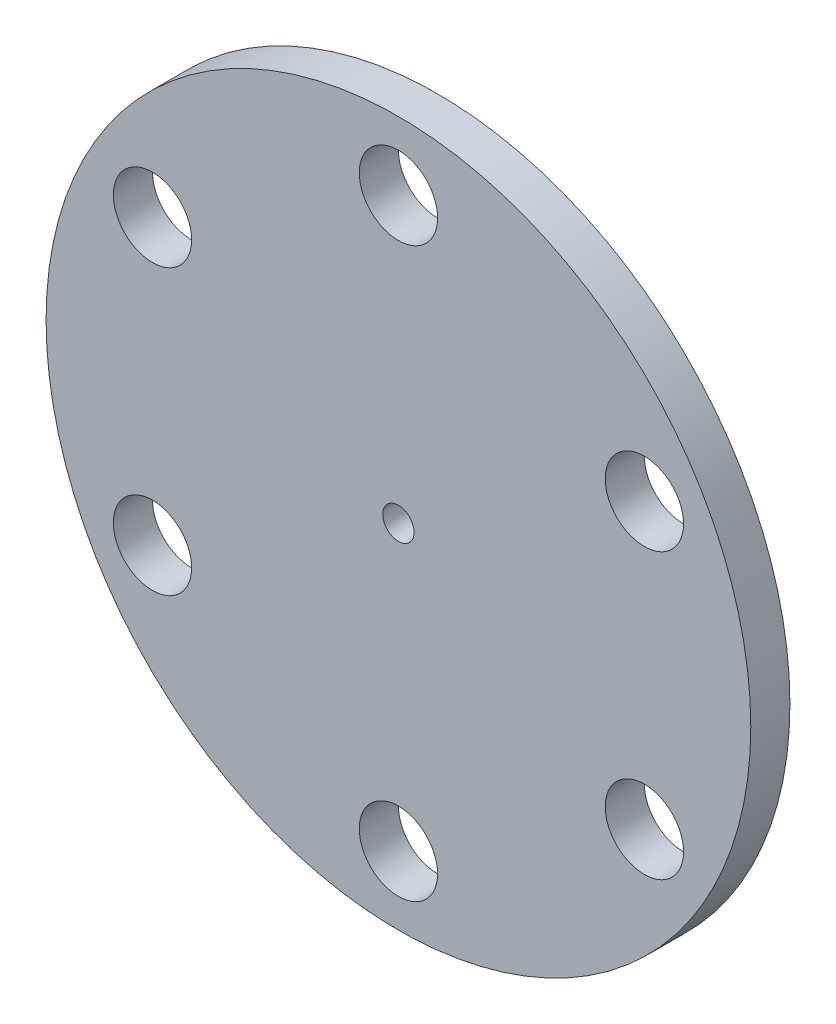
SolidWorks part; units mm, degrees
ref_plane "Front Plane" through (0, 0, 0) normal (0, 0, 1) x (1, 0, 0)
ref_plane "Top Plane" through (0, 0, 0) normal (0, 1, 0) x (1, 0, 0)
ref_plane "Right Plane" through (0, 0, 0) normal (1, 0, 0) x (0, 0, -1)
sketch "Sketch1" plane through (0, 0, 0) normal (0, 0, 1) x (1, 0, 0)
  line L0 (0, -55) -> (0, 55) construction
  circle A0 centre (0, 0) radius 45
  circle A1 centre (0, 36.2696) radius 5
  circle A2 centre (31.4104, 18.1348) radius 5
  circle A3 centre (31.4104, -18.1348) radius 5
  circle A4 centre (0, -36.2696) radius 5
  circle A5 centre (-31.4104, -18.1348) radius 5
  circle A6 centre (-31.4104, 18.1348) radius 5
  circle A7 centre (0, 0) radius 2
  point P19 (0, 0)
  dimension "D1" = 6
extrude "Boss-Extrude1" add sketch "Sketch1" along normal blind 5
